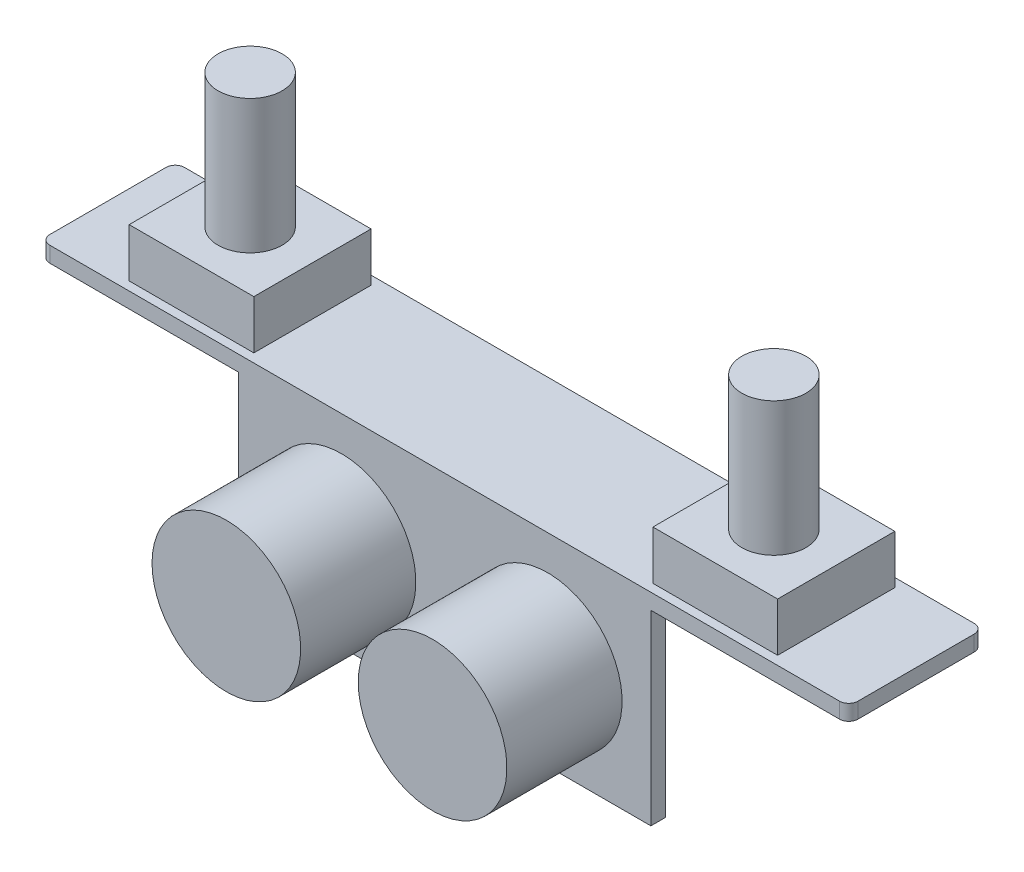
SolidWorks part; units mm, degrees
ref_plane "Front Plane" through (0, 0, 0) normal (0, 0, 1) x (1, 0, 0)
ref_plane "Top Plane" through (0, 0, 0) normal (0, 1, 0) x (1, 0, 0)
ref_plane "Right Plane" through (0, 0, 0) normal (1, 0, 0) x (0, 0, -1)
sketch "Sketch1" plane through (0, 0, 0) normal (0, 1, 0) x (1, 0, 0)
  line L1 (-42.5, 7.25) -> (42.5, 7.25)
  line L2 (-43.5, 6.25) -> (-43.5, -6.25)
  line L3 (-42.5, -7.25) -> (42.5, -7.25)
  line L4 (43.5, 6.25) -> (43.5, -6.25)
  line L5 (0, -7.25) -> (0, 7.25) construction
  line L6 (-43.5, 0) -> (43.5, 0) construction
  arc A0 (42.5, 7.25) -> (43.5, 6.25) centre (42.5, 6.25) cw
  arc A1 (42.5, -7.25) -> (43.5, -6.25) centre (42.5, -6.25) ccw
  arc A2 (-43.5, -6.25) -> (-42.5, -7.25) centre (-42.5, -6.25) ccw
  arc A3 (-42.5, 7.25) -> (-43.5, 6.25) centre (-42.5, 6.25) ccw
  point P6 (43.5, 7.25)
  point P11 (-43.5, -7.25)
  point P14 (-43.5, 7.25)
  point P15 (0, 0)
  point P76 (0, 0)
  dimension "D1" = 1
  dimension "8.7" = 87
  dimension "1.45" = 14.5
extrude "Boss-Extrude1" add sketch "Sketch1" along normal blind 1.68
sketch "Sketch3" plane through (0, 1.68, 0) normal (0, 1, 0) x (1, 0, 0)
  line L0 (0, 7.25) -> (0, -7.25) construction
  line L1 (42.5, 7.25) -> (-42.5, 7.25) construction
  line L2 (-42.5, -7.25) -> (42.5, -7.25) construction
  line L3 (-43.5, 0) -> (43.5, 0) construction
  line L4 (-43.5, 6.25) -> (-43.5, -6.25) construction
  line L5 (43.5, -6.25) -> (43.5, 6.25) construction
  line L6 (34.9, -6.31) -> (21.48, -6.31)
  line L7 (-34.9, 6.31) -> (-21.48, 6.31)
  line L8 (-34.9, 6.31) -> (-34.9, -6.31)
  line L9 (-34.9, -6.31) -> (-21.48, -6.31)
  line L10 (-21.48, 6.31) -> (-21.48, -6.31)
  line L11 (-28.19, -6.31) -> (-28.19, 6.31) construction
  line L12 (-34.9, 0) -> (-21.48, 0) construction
  line L13 (21.48, 6.31) -> (21.48, -6.31)
  line L18 (34.9, 6.31) -> (21.48, 6.31)
  line L19 (34.9, 6.31) -> (34.9, -6.31)
  point P16 (0, 0)
  point P17 (0, 0)
  point P18 (-27.785, -4.7391)
  point P19 (0, 0)
  point P48 (-28.19, 0)
  dimension "D1" = 13.42
  dimension "D2" = 12.62
  dimension ".86" = 8.6
extrude "Boss-Extrude2" add sketch "Sketch3" along normal blind 5.25
sketch "Sketch4" plane through (0, 6.93, 0) normal (0, 1, 0) x (1, 0, 0)
  line L0 (0, 7.25) -> (0, -7.25) construction
  line L1 (42.5, 7.25) -> (-42.5, 7.25) construction
  line L2 (-42.5, -7.25) -> (42.5, -7.25) construction
  line L3 (-28.19, -6.31) -> (-28.19, 6.31) construction
  line L4 (-34.9, -6.31) -> (-21.48, -6.31) construction
  line L5 (-21.48, 6.31) -> (-34.9, 6.31) construction
  line L6 (-28.19, 0) -> (-21.48, 0) construction
  line L7 (-21.48, -6.31) -> (-21.48, 6.31) construction
  circle A0 centre (-28.19, 0) radius 3.45
  circle A1 centre (28.19, 0) radius 3.45
extrude "Boss-Extrude3" add sketch "Sketch4" along normal blind 14.4
sketch "Sketch5" plane through (0, 0, 7.25) normal (0, 0, 1) x (1, 0, 0)
  line L0 (0, 0) -> (0, -25.292) construction
  line L1 (-42.5, 0) -> (42.5, 0) construction
  line L2 (-22.2, 0) -> (22.2, 0)
  line L3 (-22.2, 0) -> (-22.2, -20.1)
  line L4 (-22.2, -20.1) -> (22.2, -20.1)
  line L5 (22.2, 0) -> (22.2, -20.1)
  line L6 (0, -20.1) -> (0, 0) construction
  line L7 (-22.2, -10.05) -> (22.2, -10.05) construction
  line L8 (-43.5, 1.68) -> (-43.5, 0) construction
  line L9 (43.5, 1.68) -> (43.5, 0) construction
  point P9 (0, 0)
  point P10 (0, 0)
  point P11 (0, 0)
  point P12 (0, 0)
  point P13 (23.9251, -15.8516)
  point P247 (0, -10.05)
  dimension "D1" = 21.3
  dimension "D2" = 21.3
  dimension "D3" = 44.4
  dimension "20.1mm" = 20.1
extrude "Boss-Extrude4" add sketch "Sketch5" against normal blind 1.6
sketch "Sketch6" plane through (0, 0, 7.25) normal (0, 0, 1) x (1, 0, 0)
  line L0 (22.2, 0) -> (-22.2, 0) construction
  line L1 (0, 0) -> (0, -20.1) construction
  line L2 (-22.2, -20.1) -> (22.2, -20.1) construction
  line L3 (0, -10.05) -> (22.2, -10.05) construction
  line L4 (22.2, -20.1) -> (22.2, 0) construction
  circle A0 centre (11.1, -10.05) radius 8
  circle A1 centre (-11.1, -10.05) radius 8
  point P15 (19.1, -10.05)
  dimension "D1" = 16
extrude "Boss-Extrude5" add sketch "Sketch6" along normal blind 12.4
